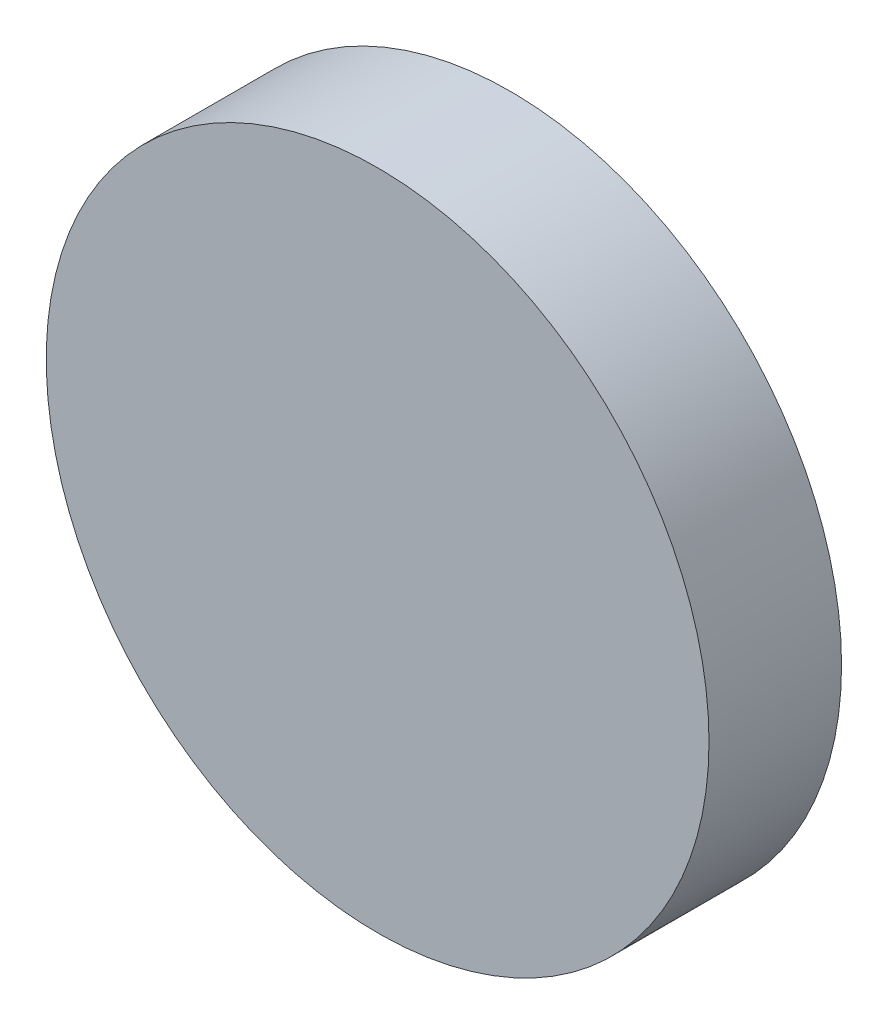
SolidWorks part; units mm, degrees
material "AISI 1020"
ref_plane "Ebene vorne" through (0, 0, 0) normal (0, 0, 1) x (1, 0, 0)
ref_plane "Ebene oben" through (0, 0, 0) normal (0, 1, 0) x (1, 0, 0)
ref_plane "Ebene rechts" through (0, 0, 0) normal (1, 0, 0) x (0, 0, -1)
sketch "Skizze2" plane through (0, 0, 0) normal (0, 0, 1) x (1, 0, 0)
  circle A0 centre (0, 0) radius 5
  dimension "D1" = 10
extrude "Aufsatz-Linear austragen1" add sketch "Skizze2" along normal blind 2
